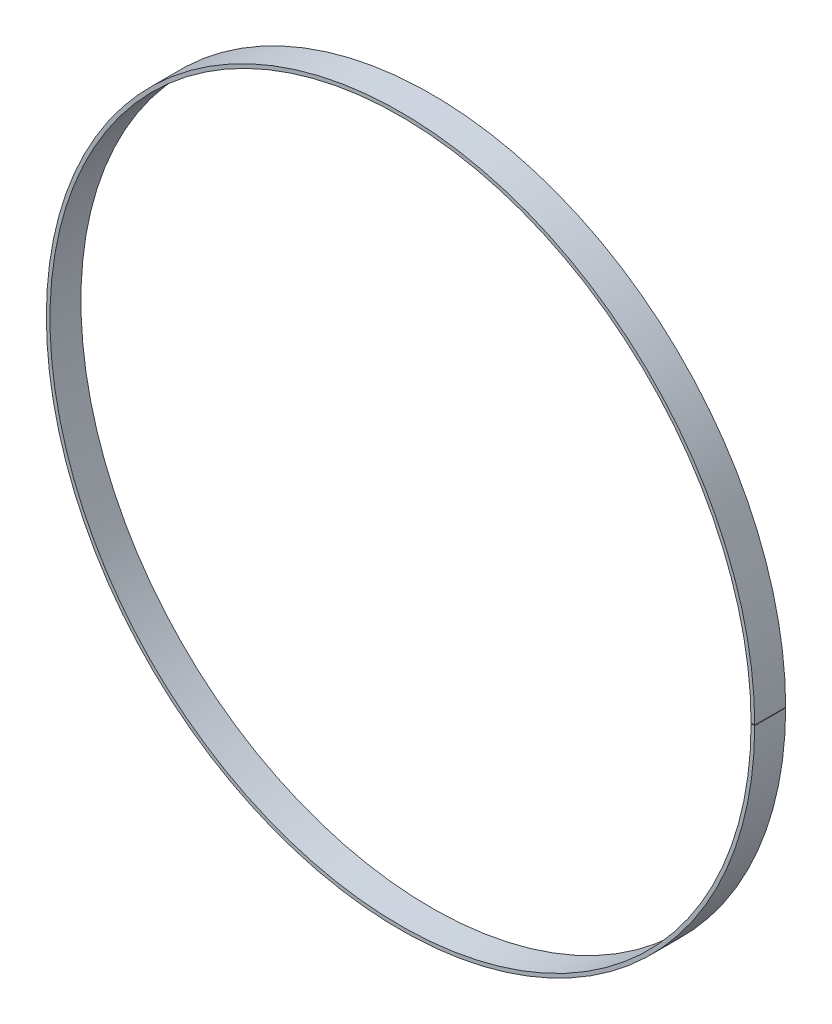
SolidWorks part; units mm, degrees
ref_plane "Plan de face" through (0, 0, 0) normal (0, 0, 1) x (1, 0, 0)
ref_plane "Plan de dessus" through (0, 0, 0) normal (0, 1, 0) x (1, 0, 0)
ref_plane "Plan de droite" through (0, 0, 0) normal (1, 0, 0) x (0, 0, -1)
sketch "Esquisse1" plane through (0, 0, 0) normal (0, 0, 1) x (1, 0, 0)
  line L0 (0, 0) -> (152.9999, 0.1237) construction
  line L1 (0, 0) -> (152.9999, -0.1237) construction
  line L2 (152.9999, 0.1237) -> (154.5874, 0.125)
  line L3 (152.9999, -0.1237) -> (154.5874, -0.125)
  line L4 (154.5874, 0.125) -> (154.5874, -0.125) construction
  arc A0 (152.9999, 0.1237) -> (152.9999, -0.1237) centre (0, 0) ccw
  arc A1 (154.5874, 0.125) -> (154.5874, -0.125) centre (0, 0) ccw
  dimension "D1" = 153
  dimension "D3" = 1.5875
  dimension "D2" = 0.25
extrude "Boss.-Extru.1" add sketch "Esquisse1" along normal blind 13.5
